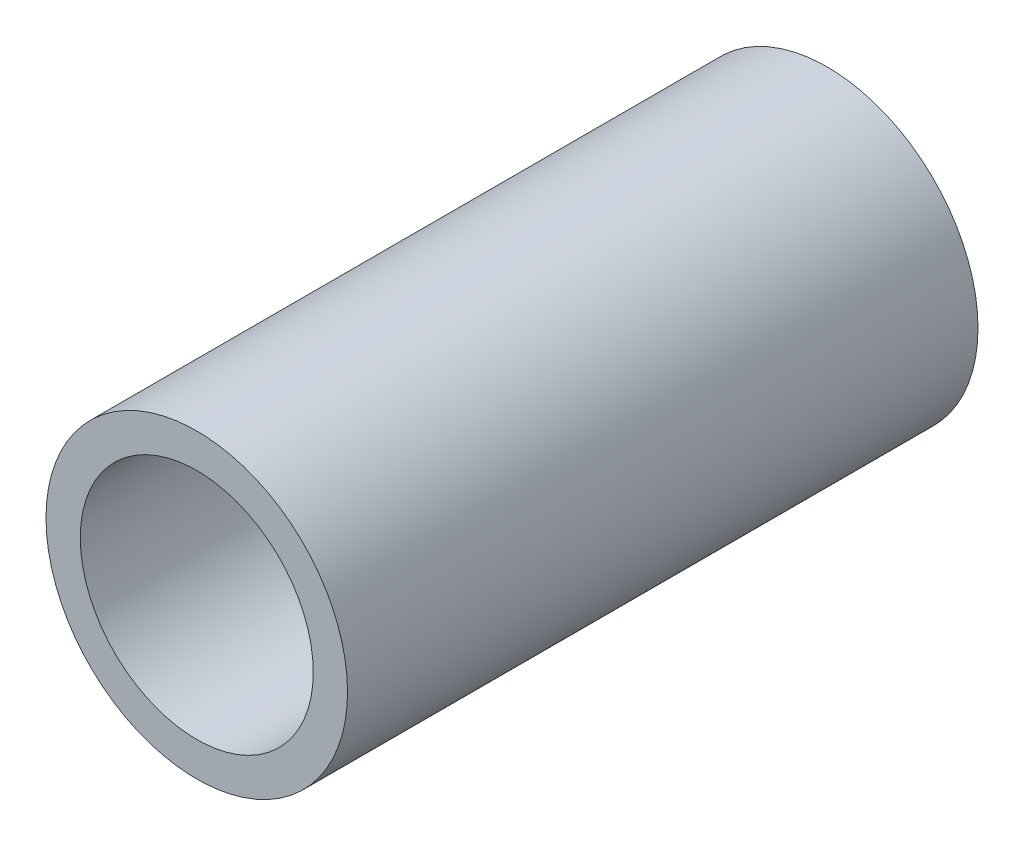
SolidWorks part; units mm, degrees
ref_plane "Alzado" through (0, 0, 0) normal (0, 0, 1) x (1, 0, 0)
ref_plane "Planta" through (0, 0, 0) normal (0, 1, 0) x (1, 0, 0)
ref_plane "Vista lateral" through (0, 0, 0) normal (1, 0, 0) x (0, 0, -1)
sketch "Croquis1" plane through (0, 0, 0) normal (0, 0, 1) x (1, 0, 0)
  circle A0 centre (0, 0) radius 4.25
  circle A1 centre (0, 0) radius 5.5
  dimension "D1" = 8.5
  dimension "D2" = 11
extrude "Saliente-Extruir1" add sketch "Croquis1" along normal blind 23
